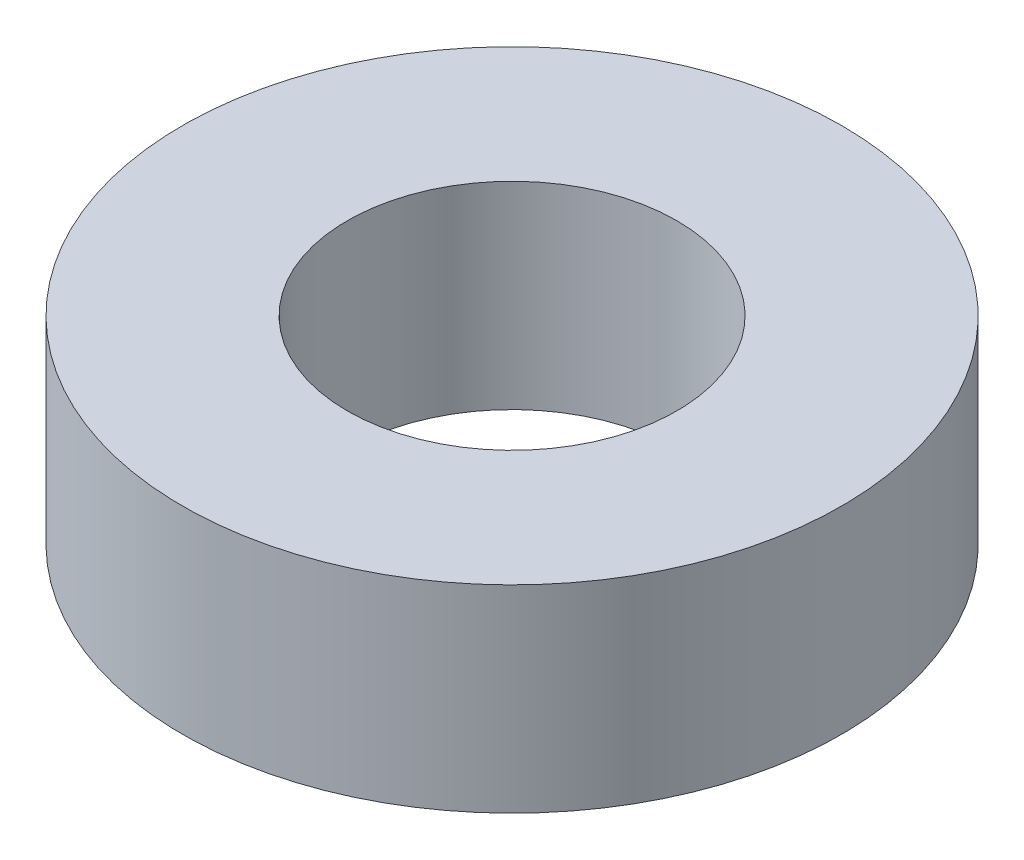
SolidWorks part; units mm, degrees
material "Alloy Steel (SS)"
ref_plane "Front Plane" through (0, 0, 0) normal (0, 0, 1) x (1, 0, 0)
ref_plane "Top Plane" through (0, 0, 0) normal (0, 1, 0) x (1, 0, 0)
ref_plane "Right Plane" through (0, 0, 0) normal (1, 0, 0) x (0, 0, -1)
sketch "Sketch1" plane through (0, 0, 0) normal (0, 1, 0) x (1, 0, 0)
  circle A0 centre (0, 0) radius 3.175
  circle A1 centre (0, 0) radius 6.35
  dimension "D1" = 6.35
  dimension "D2" = 12.7
extrude "Boss-Extrude1" add sketch "Sketch1" along normal blind 3.81
